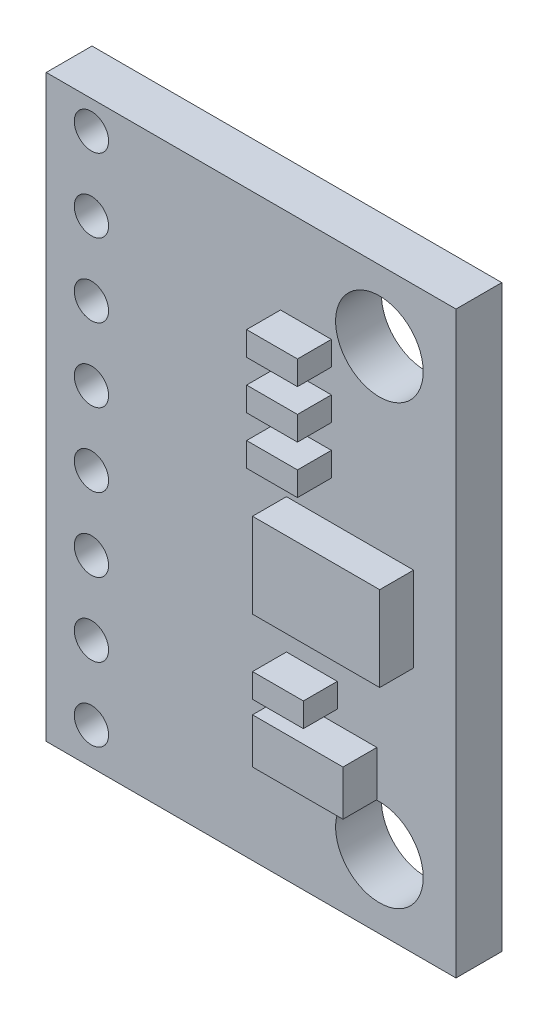
SolidWorks part; units mm, degrees
ref_plane "Front Plane" through (0, 0, 0) normal (0, 0, 1) x (1, 0, 0)
ref_plane "Top Plane" through (0, 0, 0) normal (0, 1, 0) x (1, 0, 0)
ref_plane "Right Plane" through (0, 0, 0) normal (1, 0, 0) x (0, 0, -1)
sketch "Sketch1" plane through (0, 0, 0) normal (0, 0, 1) x (1, 0, 0)
  line L1 (-7.25, -10.25) -> (7.25, -10.25)
  line L2 (-7.25, -10.25) -> (-7.25, 10.25)
  line L3 (-7.25, 10.25) -> (7.25, 10.25)
  line L4 (7.25, -10.25) -> (7.25, 10.25)
  line L5 (-7.25, -10.25) -> (7.25, 10.25) construction
  line L6 (-7.25, 10.25) -> (7.25, -10.25) construction
  point P0 (0, 0)
  dimension "D1" = 14.5
  dimension "D2" = 20.5
extrude "Boss-Extrude1" add sketch "Sketch1" along normal blind 1.62
sketch "Sketch2" plane through (0, 0, 1.62) normal (0, 0, 1) x (1, 0, 0)
  line L0 (4.54, -7.75) -> (4.54, 7.75) construction
  line L3 (4.54, 7.75) -> (6.09, 7.75) construction
  line L4 (7.25, -10.25) -> (7.25, 10.25) construction
  circle A0 centre (4.54, 7.75) radius 1.55
  circle A1 centre (4.54, -7.75) radius 1.55
  point P3 (4.54, 0)
  point P5 (6.09, 7.75)
  dimension "D3" = 3.1
  dimension "D2" = 1.16
  dimension "D1" = 15.5
extrude "Cut-Extrude1" cut sketch "Sketch2" against normal blind 1.62
sketch "Sketch3" plane through (0, 0, 1.62) normal (0, 0, 1) x (1, 0, 0)
  line L0 (7.25, -10.25) -> (7.25, 10.25) construction
  line L1 (1.04, 7.1152) -> (2.84, 7.1152)
  line L2 (1.04, 7.1152) -> (1.04, 6.2652)
  line L3 (1.04, 6.2652) -> (2.84, 6.2652)
  line L4 (2.84, 7.1152) -> (2.84, 6.2652)
  line L5 (1.04, 7.1152) -> (2.84, 6.2652) construction
  line L6 (1.04, 6.2652) -> (2.84, 7.1152) construction
  line L7 (1.04, 5.4152) -> (2.84, 5.4152)
  line L8 (1.04, 5.4152) -> (1.04, 4.5652)
  line L9 (1.04, 4.5652) -> (2.84, 4.5652)
  line L10 (2.84, 5.4152) -> (2.84, 4.5652)
  line L11 (1.04, 5.4152) -> (2.84, 4.5652) construction
  line L12 (1.04, 4.5652) -> (2.84, 5.4152) construction
  line L13 (1.04, 3.7152) -> (2.84, 3.7152)
  line L14 (1.04, 3.7152) -> (1.04, 2.8652)
  line L15 (1.04, 2.8652) -> (2.84, 2.8652)
  line L16 (2.84, 3.7152) -> (2.84, 2.8652)
  line L17 (1.04, 3.7152) -> (2.84, 2.8652) construction
  line L18 (1.04, 2.8652) -> (2.84, 3.7152) construction
  line L23 (1.94, 6.6902) -> (1.94, 4.9902) construction
  line L24 (5.75, -1.5) -> (1.25, -1.5)
  line L25 (1.25, 10.25) -> (1.25, -10.25) construction
  line L26 (1.25, -4.1098) -> (3.05, -4.1098)
  line L27 (1.25, -4.1098) -> (1.25, -3.2598)
  line L28 (1.25, -3.2598) -> (3.05, -3.2598)
  line L29 (3.05, -4.1098) -> (3.05, -3.2598)
  line L30 (1.25, -4.1098) -> (3.05, -3.2598) construction
  line L31 (1.25, -3.2598) -> (3.05, -4.1098) construction
  line L32 (1.25, -4.5848) -> (4.45, -4.5848)
  line L33 (1.25, -4.5848) -> (1.25, -6.1848)
  line L34 (1.25, -6.1848) -> (4.45, -6.1848)
  line L35 (4.45, -4.5848) -> (4.45, -6.1848)
  line L36 (1.25, -4.5848) -> (4.45, -6.1848) construction
  line L37 (1.25, -6.1848) -> (4.45, -4.5848) construction
  line L38 (7.25, 10.25) -> (-7.25, 10.25) construction
  line L39 (-7.25, -10.25) -> (7.25, -10.25) construction
  line L40 (5.75, -1.5) -> (5.75, 1.5)
  line L41 (5.75, 1.5) -> (1.25, 1.5)
  line L42 (1.25, -1.5) -> (1.25, 1.5)
  line L43 (5.75, -1.5) -> (1.25, 1.5) construction
  line L44 (5.75, 1.5) -> (1.25, -1.5) construction
  line L45 (1.94, 3.2902) -> (1.94, 4.9902) construction
  point P0 (1.94, 6.6902)
  point P5 (1.94, 4.9902)
  point P10 (1.94, 3.2902)
  point P15 (3.5, 0)
  point P22 (2.15, -3.6848)
  point P27 (2.85, -5.3848)
  dimension "D1" = 1.8
  dimension "D2" = 0.85
  dimension "D3" = 6
  dimension "D4" = 4.5
  dimension "D5" = 3
  dimension "D6" = 3.2
  dimension "D7" = 1.6
  dimension "D8" = 13.3
  dimension "D9" = 1.7
  dimension "D10" = 1.7
extrude "Boss-Extrude2" add sketch "Sketch3" along normal blind 1.2
sketch "Sketch4" plane through (0, 0, 1.62) normal (0, 0, 1) x (1, 0, 0)
  line L0 (-5.65, -10.25) -> (-5.65, 10.25) construction
  line L1 (-7.25, 10.25) -> (-7.25, -10.25) construction
  line L2 (7.25, 10.25) -> (-7.25, 10.25) construction
  line L3 (-7.25, -10.25) -> (7.25, -10.25) construction
  circle A0 centre (-5.65, 9.25) radius 0.6072
  circle A1 centre (-5.65, 6.65) radius 0.6072
  circle A2 centre (-5.65, 4.05) radius 0.6072
  circle A3 centre (-5.65, 1.45) radius 0.6072
  circle A4 centre (-5.65, -1.15) radius 0.6072
  circle A5 centre (-5.65, -3.75) radius 0.6072
  circle A6 centre (-5.65, -6.35) radius 0.6072
  circle A7 centre (-5.65, -8.95) radius 0.6072
  circle A8 centre (-5.65, -11.55) radius 0.6072
  circle A9 centre (-5.65, -14.15) radius 0.6072
  point P3 (-5.65, 0)
  dimension "D1" = 1.6
  dimension "D3" = 1
  dimension "D2" = 10
extrude "Cut-Extrude2" cut sketch "Sketch4" against normal through all
